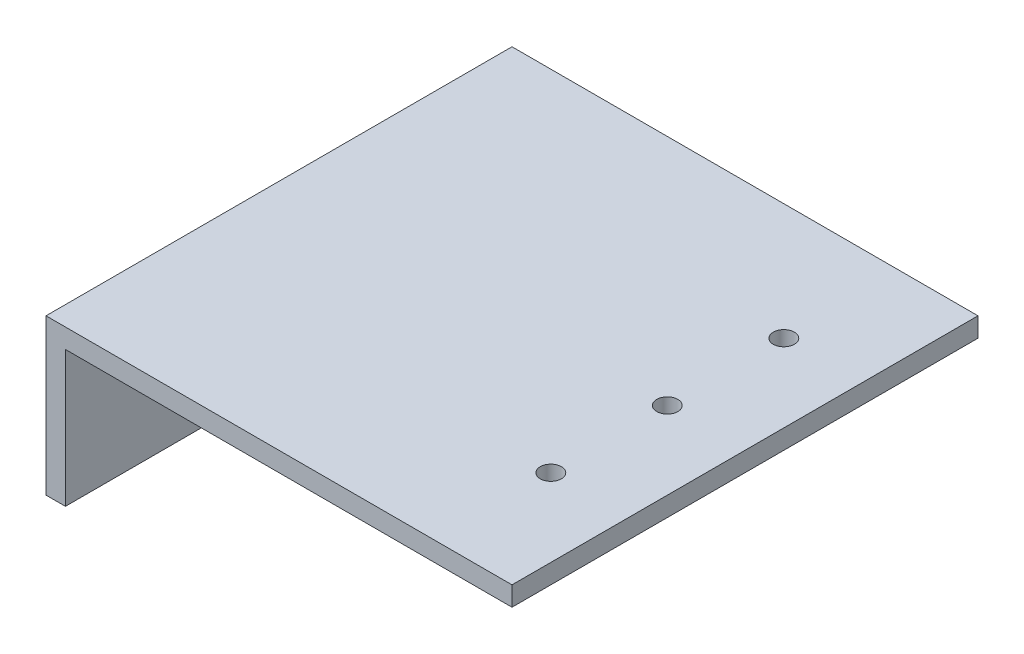
SolidWorks part; units mm, degrees
ref_plane "Front Plane" through (0, 0, 0) normal (0, 0, 1) x (1, 0, 0)
ref_plane "Top Plane" through (0, 0, 0) normal (0, 1, 0) x (1, 0, 0)
ref_plane "Right Plane" through (0, 0, 0) normal (1, 0, 0) x (0, 0, -1)
sketch "Sketch2" plane through (0, 0, 0) normal (0, 0, 1) x (1, 0, 0)
  line L0 (0, 0) -> (-76.2, 0)
  line L1 (-76.2, 0) -> (-76.2, -25.4)
  line L2 (-76.2, -25.4) -> (-73.025, -25.4)
  line L3 (-73.025, -25.4) -> (-73.025, -3.175)
  line L4 (-73.025, -3.175) -> (0, -3.175)
  line L5 (0, -3.175) -> (0, 0)
  dimension "D1" = 76.2
  dimension "D2" = 25.4
  dimension "D3" = 3.175
  dimension "D4" = 3.175
extrude "Boss-Extrude1" add sketch "Sketch2" along normal blind 76.2
sketch "Sketch7" plane through (-76.2, 0, 0) normal (-1, 0, 0) x (0, 0, 1)
  line L1 (0, 0) -> (0, -25.4) construction
  line L2 (0, -15.24) -> (38.1, -15.24) construction
  line L7 (36.449, -16.9885) -> (39.751, -13.4915) construction
  line L8 (36.449, -13.4915) -> (39.751, -16.9885) construction
  circle A0 centre (38.1, -15.24) radius 3.175
  dimension "D1" = 38.1
  dimension "D2" = 3.302
extrude "Cut-Extrude1" cut sketch "Sketch7" against normal up to next
hole_wizard "Tap Drill for #8-32 Tap2" positions "Sketch10" profile "Sketch9" hole size "#8-32" standard "ANSI Inch" end condition through all
sketch "Sketch10" plane through (0, 0, 0) normal (0, 1, 0) x (1, 0, 0)
  line L0 (0, 0) -> (-76.2, 0) construction
  line L1 (0, -76.2) -> (0, 0) construction
  point P0 (-12.7, -19.05)
  point P2 (-12.7, -38.1)
  point P4 (-12.7, -57.15)
  dimension "D1" = 19.05
  dimension "D2" = 19.05
  dimension "D3" = 19.05
  dimension "D4" = 12.7
sketch "Sketch9" plane through (-12.7, 0, 19.05) normal (1, 0, 0) x (0, 0, 1)
  line L0 (0, 0) -> (0, 25.4)
  line L1 (0, 25.4) -> (1.7272, 25.4)
  line L2 (1.7272, 25.4) -> (1.7272, 0)
  line L5 (1.7272, 0) -> (0, 0)
  line L11 (0, -6.35) -> (0, 107.95) construction
  dimension "Thru Hole Dia." = 3.4544
  dimension "Thru Hole Depth" = 25.4
hole_wizard "Tap Drill for #8-32 Tap3" positions "Sketch12" profile "Sketch11" hole size "#8-32" standard "ANSI Inch" end condition up to next
sketch "Sketch12" plane through (-76.2, 0, 0) normal (-1, 0, 0) x (0, 0, 1)
  line L0 (38.1, -15.24) -> (25.4, -15.24) construction
  circle A0 centre (38.1, -15.24) radius 3.175 construction
  point P0 (25.4, -15.24)
  point P2 (50.8, -15.24)
  dimension "D1" = 12.7
  dimension "D2" = 12.7
sketch "Sketch11" plane through (-76.2, -15.24, 25.4) normal (0, 1, 0) x (0, 0, 1)
  line L0 (0, 0) -> (0, 3.175)
  line L1 (0, 3.175) -> (1.7272, 3.175)
  line L2 (1.7272, 3.175) -> (1.7272, 0)
  line L5 (1.7272, 0) -> (0, 0)
  line L11 (0, -6.35) -> (0, 107.95) construction
  dimension "Thru Hole Dia." = 3.4544
  dimension "Thru Hole Depth" = 3.175
